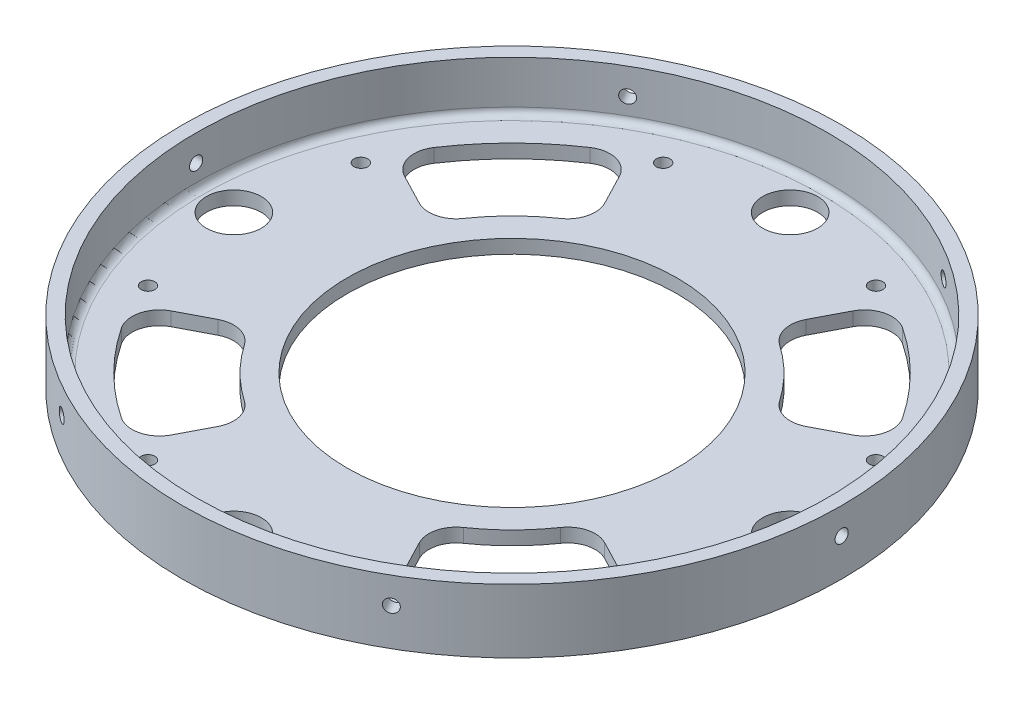
SolidWorks part; units mm, degrees
material "6061-T6 (SS)"
ref_plane "Front Plane" through (0, 0, 0) normal (0, 0, 1) x (1, 0, 0)
ref_plane "Top Plane" through (0, 0, 0) normal (0, 1, 0) x (1, 0, 0)
ref_plane "Right Plane" through (0, 0, 0) normal (1, 0, 0) x (0, 0, -1)
sketch "Sketch1" plane through (0, 0, 0) normal (0, 1, 0) x (1, 0, 0)
  circle A0 centre (0, 0) radius 76.2
extrude "Boss-Extrude1" add sketch "Sketch1" along normal blind 16.256
shell "Shell1" thickness 3.175
fillet "Fillet1" radius 1.5875 1 edges at (0, 3.175, 73.025)
sketch "Sketch2" plane through (0, 0, 0) normal (0, -1, 0) x (1, 0, 0)
  circle A0 centre (0, 0) radius 38.1
  dimension "D1" = 76.2
extrude "Cut-Extrude1" cut sketch "Sketch2" against normal blind 16.256
sketch "Sketch3" plane through (0, 0, 0) normal (1, 0, 0) x (0, 0, -1)
  line L0 (0, 0) -> (0, 8.636) construction
  circle A0 centre (0, 8.636) radius 1.524
  dimension "D2" = 3.048
  dimension "D1" = 8.636
extrude "Cut-Extrude2" cut sketch "Sketch3" against normal blind 76.2
pattern_circular "CirPattern1" count 6 over 360 about axis through (0, 16.256, 0) along (0, -1, 0) of "Cut-Extrude2"
sketch "Sketch5" plane through (0, 16.256, 0) normal (0, 1, 0) x (1, 0, 0)
  circle A0 centre (0, 0) radius 76.2
extrude "Cut-Extrude4" cut sketch "Sketch5" against normal blind 1.524
sketch "Sketch6" plane through (0, 3.175, 0) normal (0, 1, 0) x (1, 0, 0)
  line L0 (0, 0) -> (0, 71.4375) construction
  line L1 (0, 0) -> (61.8667, 35.7187) construction
  line L2 (0, 0) -> (61.8667, -35.7188) construction
  line L3 (0, 0) -> (0, -71.4375) construction
  line L4 (0, 0) -> (-61.8667, -35.7187) construction
  line L5 (0, 0) -> (-61.8667, 35.7188) construction
  circle A0 centre (0, 0) radius 71.4375 construction
  circle A1 centre (0, 0) radius 73.025 construction
  circle A2 centre (0, 64.2874) radius 6.35
  circle A3 centre (0, -64.2874) radius 6.35
  point P15 (0, 0)
  dimension "D2" = 64.2874
  dimension "D4" = 12.7
  dimension "D5" = 12.7
  dimension "D3" = 64.2874
  dimension "D1" = 6
extrude "Cut-Extrude5" cut sketch "Sketch6" against normal blind 12.7
sketch "Sketch7" plane through (0, 3.175, 0) normal (0, 1, 0) x (1, 0, 0)
  line L0 (0, 0) -> (0, 59.525) construction
  line L1 (24.6, 59.525) -> (-24.6, 59.525) construction
  line L2 (0, 0) -> (-76.2, 0) construction
  line L3 (24.6, -59.525) -> (-24.6, -59.525) construction
  line L4 (0, 0) -> (0, -59.525) construction
  line L5 (0, 0) -> (53.8815, 53.8815) construction
  line L6 (-59.525, 24.6) -> (-59.525, -24.6) construction
  line L7 (59.525, 24.6) -> (59.525, -24.6) construction
  line L8 (-59.525, 0) -> (59.525, 0) construction
  circle A0 centre (-24.6, 59.525) radius 1.5875
  circle A1 centre (24.6, 59.525) radius 1.5875
  circle A2 centre (0, 0) radius 76.2 construction
  circle A3 centre (24.6, -59.525) radius 1.5875
  circle A4 centre (-24.6, -59.525) radius 1.5875
  circle A5 centre (-59.525, -24.6) radius 1.5875
  circle A6 centre (-59.525, 24.6) radius 1.5875
  circle A7 centre (59.525, 24.6) radius 1.5875
  circle A8 centre (59.525, -24.6) radius 1.5875
  dimension "D1" = 3.175
  dimension "D2" = 24.6
  dimension "D3" = 59.525
extrude "Cut-Extrude6" cut sketch "Sketch7" against normal blind 6.35
sketch "Sketch8" plane through (0, 3.175, 0) normal (0, 1, 0) x (1, 0, 0)
  line L0 (-76.2, 0) -> (76.2, 0) construction
  line L1 (0, 0) -> (53.8815, 53.8815) construction
  circle A0 centre (0, 0) radius 76.2 construction
  circle A1 centre (0, 64.2874) radius 6.35
  circle A2 centre (0, -64.2874) radius 6.35
  circle A3 centre (64.2874, 0) radius 6.35
  circle A4 centre (-64.2874, 0) radius 6.35
extrude "Cut-Extrude7" cut sketch "Sketch8" against normal blind 6.35
sketch "Sketch9" plane through (0, 3.175, 0) normal (0, 1, 0) x (1, 0, 0)
  line L0 (0, 0) -> (-57.7333, 30.0541) construction
  line L1 (0, 0) -> (-30.0541, 57.7333) construction
  line L2 (0, 0) -> (-76.2, 0) construction
  line L3 (0, 0) -> (0, 76.2) construction
  line L4 (-39.4276, 20.5247) -> (-57.7333, 30.0541)
  line L5 (-20.5247, 39.4276) -> (-30.0541, 57.7333)
  line L6 (-20.5247, -39.4276) -> (-30.0541, -57.7333)
  line L7 (-39.4276, -20.5247) -> (-57.7333, -30.0541)
  line L8 (39.4276, -20.5247) -> (57.7333, -30.0541)
  line L9 (20.5247, -39.4276) -> (30.0541, -57.7333)
  line L10 (20.5247, 39.4276) -> (30.0541, 57.7333)
  line L11 (39.4276, 20.5247) -> (57.7333, 30.0541)
  circle A0 centre (0, 0) radius 71.4375 construction
  circle A1 centre (0, 0) radius 38.1 construction
  arc A2 (-20.5247, 39.4276) -> (-39.4276, 20.5247) centre (0, 0) ccw
  arc A3 (-30.0541, 57.7333) -> (-57.7333, 30.0541) centre (0, 0) ccw
  circle A4 centre (0, 0) radius 76.2 construction
  arc A5 (-30.0541, -57.7333) -> (-57.7333, -30.0541) centre (0, 0) cw
  arc A6 (-20.5247, -39.4276) -> (-39.4276, -20.5247) centre (0, 0) cw
  arc A7 (20.5247, -39.4276) -> (39.4276, -20.5247) centre (0, 0) ccw
  arc A8 (30.0541, -57.7333) -> (57.7333, -30.0541) centre (0, 0) ccw
  arc A9 (30.0541, 57.7333) -> (57.7333, 30.0541) centre (0, 0) cw
  arc A10 (20.5247, 39.4276) -> (39.4276, 20.5247) centre (0, 0) cw
  dimension "D1" = 142.875
  dimension "D2" = 76.2
  dimension "D3" = 6.35
  dimension "D4" = 6.35
  dimension "D5" = 27.5
  dimension "D6" = 27.5
extrude "Cut-Extrude8" cut sketch "Sketch9" against normal blind 6.35
fillet "Fillet2" radius 6.35 16 edges at (57.7333, 1.5875, -30.0541) (30.0541, 1.5875, -57.7333) (20.5247, 1.5875, -39.4276) (39.4276, 1.5875, -20.5247) (57.7333, 1.5875, 30.0541) (30.0541, 1.5875, 57.7333) (39.4276, 1.5875, 20.5247) (20.5247, 1.5875, 39.4276) (-20.5247, 1.5875, 39.4276) (-30.0541, 1.5875, 57.7333) (-57.7333, 1.5875, 30.0541) (-39.4276, 1.5875, 20.5247) (-20.5247, 1.5875, -39.4276) (-30.0541, 1.5875, -57.7333) (-57.7333, 1.5875, -30.0541) (-39.4276, 1.5875, -20.5247)
